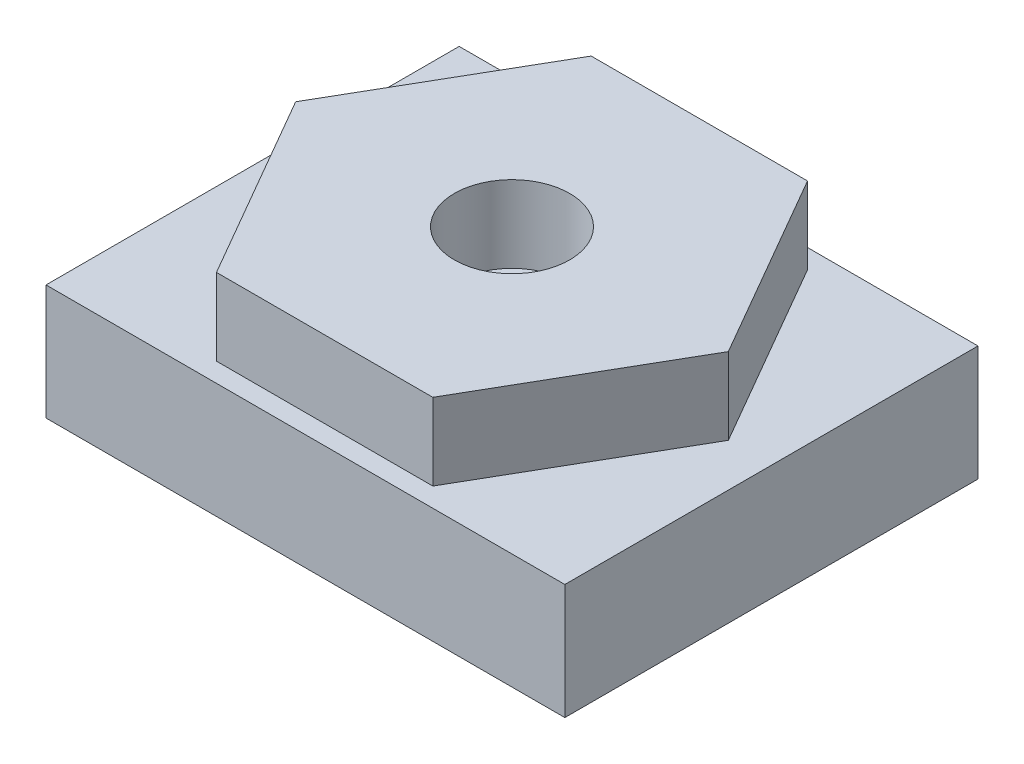
SolidWorks part; units mm, degrees
ref_plane "前视基准面" through (0, 0, 0) normal (0, 0, 1) x (1, 0, 0)
ref_plane "上视基准面" through (0, 0, 0) normal (0, 1, 0) x (1, 0, 0)
ref_plane "右视基准面" through (0, 0, 0) normal (1, 0, 0) x (0, 0, -1)
sketch "草图1" plane through (0, 0, 0) normal (0, 1, 0) x (1, 0, 0)
  line L1 (27, -21.5) -> (-27, -21.5)
  line L2 (27, -21.5) -> (27, 21.5)
  line L3 (27, 21.5) -> (-27, 21.5)
  line L4 (-27, -21.5) -> (-27, 21.5)
  line L5 (27, -21.5) -> (-27, 21.5) construction
  line L6 (27, 21.5) -> (-27, -21.5) construction
  point P0 (0, 0)
  dimension "D1" = 54
  dimension "D2" = 43
extrude "凸台-拉伸1" add sketch "草图1" along normal blind 12
sketch "草图2" plane through (0, 12, 0) normal (0, 1, 0) x (1, 0, 0)
  line L0 (0, 12.0914) -> (0, -11.6864) construction
  line L1 (-22.5167, 0) -> (-11.2583, -19.5)
  line L2 (-11.2583, -19.5) -> (11.2583, -19.5)
  line L3 (11.2583, -19.5) -> (22.5167, 0)
  line L4 (22.5167, 0) -> (11.2583, 19.5)
  line L5 (11.2583, 19.5) -> (-11.2583, 19.5)
  line L6 (-11.2583, 19.5) -> (-22.5167, 0)
  line L7 (-13.017, 0) -> (12.7856, 0) construction
  circle A0 centre (0, 0) radius 19.5 construction
  circle A1 centre (0, 0) radius 1.55
  dimension "D2" = 3.1
  dimension "D1" = 39
extrude "凸台-拉伸2" add sketch "草图2" along normal blind 8
sketch "草图4" plane through (0, 20, 0) normal (0, 1, 0) x (1, 0, 0)
  circle A0 centre (0, 0) radius 6
  dimension "D1" = 12
extrude "切除-拉伸2" cut sketch "草图4" against normal blind 8
